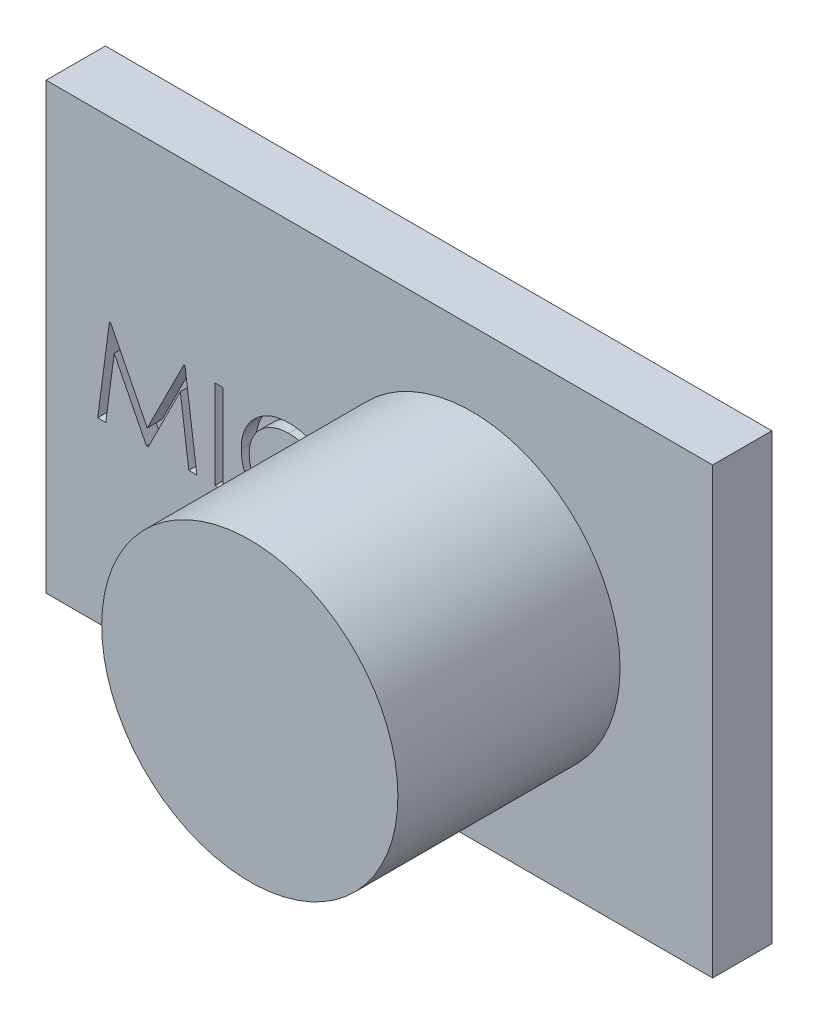
SolidWorks part; units mm, degrees
ref_plane "Front Plane" through (0, 0, 0) normal (0, 0, 1) x (1, 0, 0)
ref_plane "Top Plane" through (0, 0, 0) normal (0, 1, 0) x (1, 0, 0)
ref_plane "Right Plane" through (0, 0, 0) normal (1, 0, 0) x (0, 0, -1)
sketch "Sketch1" plane through (0, 0, 0) normal (0, 0, 1) x (1, 0, 0)
  line L1 (-11.25, 7.5) -> (11.25, 7.5)
  line L2 (-11.25, 7.5) -> (-11.25, -7.5)
  line L3 (-11.25, -7.5) -> (11.25, -7.5)
  line L4 (11.25, 7.5) -> (11.25, -7.5)
  line L5 (-11.25, 7.5) -> (11.25, -7.5) construction
  line L6 (-11.25, -7.5) -> (11.25, 7.5) construction
  point P0 (0, 0)
  dimension "D1" = 15
  dimension "D2" = 22.5
extrude "Boss-Extrude1" add sketch "Sketch1" along normal blind 2
sketch "Sketch2" plane through (0, 0, 2) normal (0, 0, 1) x (1, 0, 0)
  line L0 (0, 0) -> (11.25, 0) construction
  line L1 (11.25, -7.5) -> (11.25, 7.5) construction
  circle A0 centre (3.125, 0) radius 5
  point P2 (0, 0)
  point P8 (2.7007, 0)
  point P9 (5.625, 0)
  dimension "D1" = 10
  dimension "D2" = 2.5
extrude "Boss-Extrude2" add sketch "Sketch2" along normal blind 7.5
sketch "Sketch3" plane through (0, 0, 2) normal (0, 0, 1) x (1, 0, 0)
  line L0 (-11.25, -1.5) -> (0, -1.5) construction
  line L1 (-11.25, 7.5) -> (-11.25, -7.5) construction
  text T0 "MIC" font "Century Gothic" height 3
  dimension "D1" = 1.5
extrude "Cut-Extrude1" cut sketch "Sketch3" against normal blind 0.5
